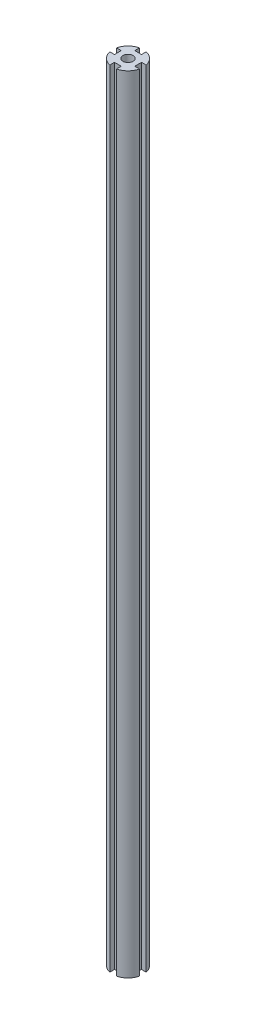
SolidWorks part; units mm, degrees
ref_plane "Front Plane" through (0, 0, 0) normal (0, 0, 1) x (1, 0, 0)
ref_plane "Top Plane" through (0, 0, 0) normal (0, 1, 0) x (1, 0, 0)
ref_plane "Right Plane" through (0, 0, 0) normal (1, 0, 0) x (0, 0, -1)
sketch "Sketch1" plane through (0, 0, 0) normal (0, 1, 0) x (1, 0, 0)
  circle A0 centre (0, 0) radius 4.5
  dimension "D1" = 9
extrude "Boss-Extrude1" add sketch "Sketch1" along normal blind 232 contours A0
sketch "Sketch2" plane through (0, 0, 0) normal (0, -1, 0) x (1, 0, 0)
  point P0 (0, 0)
hole_wizard "Ø3.0mm Dowel Hole1" positions "Sketch2" profile "Sketch3" hole size "Ø3.0" standard "ANSI Metric"
sketch "Sketch3" plane through (0, 0, 0) normal (1, 0, 0) x (0, 0, -1)
  line L0 (0, 0) -> (0, 3.9013)
  line L1 (0, 3.9013) -> (1.5, 3)
  line L2 (1.5, 3) -> (1.5, 0)
  line L5 (1.5, 0) -> (0, 0)
  line L10 (0, 3.9013) -> (-1.5, 3) construction
  line L11 (0, -6.35) -> (0, 107.95) construction
  dimension "Hole Dia." = 3
  dimension "Hole Depth" = 3
  dimension "Drill Angle" = 118
sketch "Sketch4" plane through (0, 232, 0) normal (0, 1, 0) x (1, 0, 0)
  point P0 (0, 0)
hole_wizard "Ø3.0mm Dowel Hole2" positions "Sketch4" profile "Sketch5" hole size "Ø3.0" standard "ANSI Metric"
sketch "Sketch5" plane through (0, 232, 0) normal (1, 0, 0) x (0, 0, 1)
  line L0 (0, 0) -> (0, 3.9013)
  line L1 (0, 3.9013) -> (1.5, 3)
  line L2 (1.5, 3) -> (1.5, 0)
  line L5 (1.5, 0) -> (0, 0)
  line L10 (0, 3.9013) -> (-1.5, 3) construction
  line L11 (0, -6.35) -> (0, 107.95) construction
  dimension "Hole Dia." = 3
  dimension "Hole Depth" = 3
  dimension "Drill Angle" = 118
sketch "Sketch6" plane through (0, 232, 0) normal (0, 1, 0) x (1, 0, 0)
  line L1 (-5, 1) -> (-3, 1)
  line L2 (-5, 1) -> (-5, -1)
  line L3 (-5, -1) -> (-3, -1)
  line L4 (-3, 1) -> (-3, -1)
  dimension "D1" = 3
  dimension "D2" = 2
  dimension "D3" = 1
  dimension "D4" = 2
extrude "Cut-Extrude1" cut sketch "Sketch6" along direction (0, 1, 0) on the side against the normal through all
pattern_circular "CirPattern1" count 4 over 360 about axis through (0, 0, 0) along (0, 1, 0) of "Cut-Extrude1"
